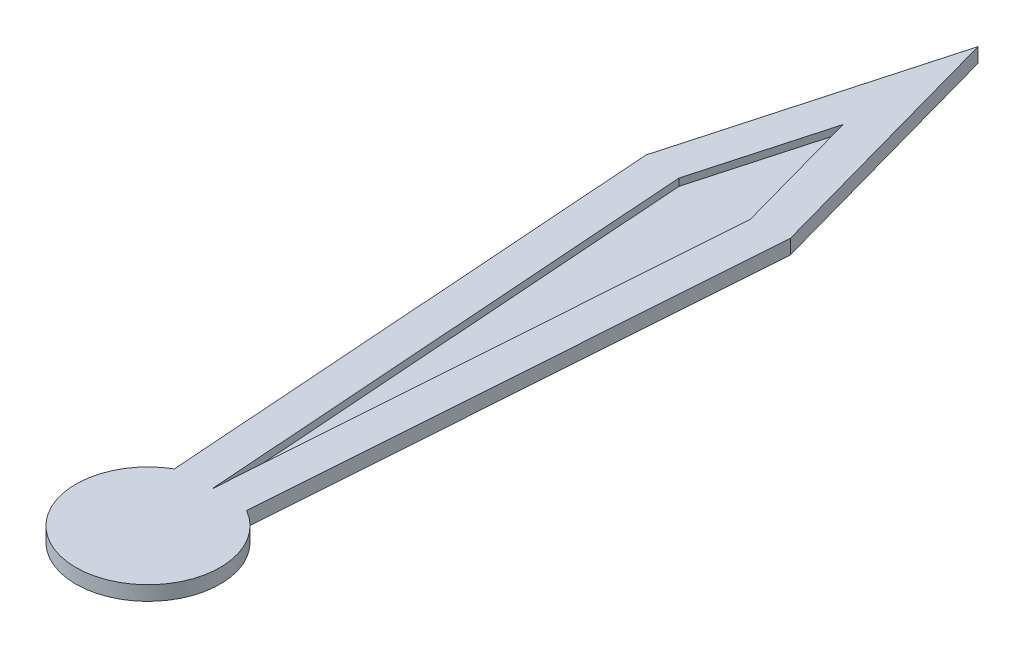
SolidWorks part; units mm, degrees
ref_plane "Front Plane" through (0, 0, 0) normal (0, 0, 1) x (1, 0, 0)
ref_plane "Top Plane" through (0, 0, 0) normal (0, 1, 0) x (1, 0, 0)
ref_plane "Right Plane" through (0, 0, 0) normal (1, 0, 0) x (0, 0, -1)
sketch "Sketch1" plane through (0, 0, 0) normal (0, 1, 0) x (1, 0, 0)
  line L0 (0, 0) -> (0, 11.5) construction
  line L1 (0, 11.5) -> (1, 7.9)
  line L2 (-1, 7.9) -> (-0.5, 0.866)
  line L3 (1, 7.9) -> (0.5, 0.866)
  line L4 (0, 11.5) -> (-1, 7.9)
  arc A0 (-0.5, 0.866) -> (0.5, 0.866) centre (0, 0) ccw
  dimension "D1" = 2
  dimension "D2" = 11.5
  dimension "D3" = 2
  dimension "D4" = 3.6
  dimension "D5" = 1
extrude "Extrude1" add sketch "Sketch1" along normal blind 0.2
sketch "Sketch2" plane through (0, 0.2, 0) normal (0, 1, 0) x (1, 0, 0)
  line L10 (-0.0013, 0.9015) -> (0.0013, 0.9015)
  line L14 (-0.4951, 7.8493) -> (-0.0013, 0.9015)
  line L15 (0.0013, 0.9015) -> (0.4951, 7.8493)
  line L16 (0.4951, 7.8493) -> (0, 9.6318)
  line L17 (0, 9.6318) -> (-0.4951, 7.8493)
  line L18 (-0.4951, 7.8493) -> (-0.0013, 0.9015)
  line L19 (0.0013, 0.9015) -> (0.4951, 7.8493)
  line L20 (0.4951, 7.8493) -> (0, 9.6318)
  line L21 (0, 9.6318) -> (-0.4951, 7.8493)
  dimension "D1" = 0.5
extrude "Extrude2" cut sketch "Sketch2" against normal blind 0.1
